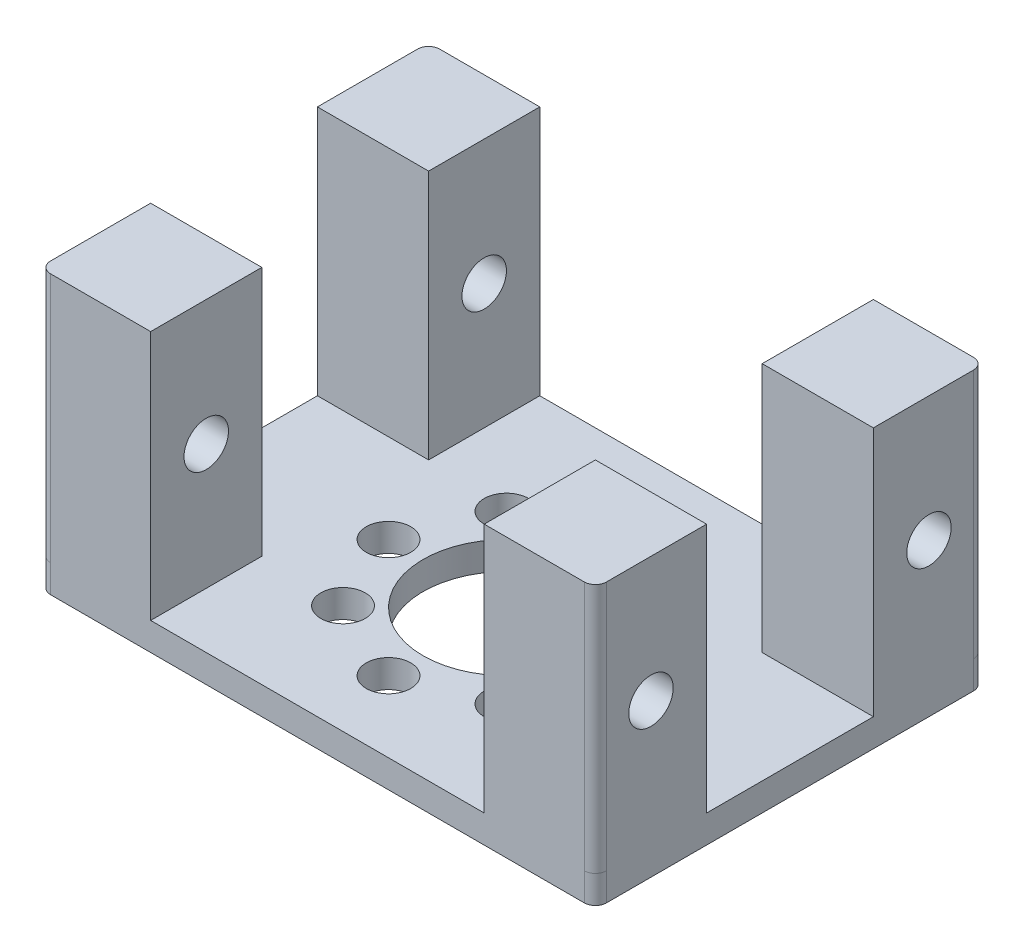
SolidWorks part; units mm, degrees
ref_plane "Front Plane" through (0, 0, 0) normal (0, 0, 1) x (1, 0, 0)
ref_plane "Top Plane" through (0, 0, 0) normal (0, 1, 0) x (1, 0, 0)
ref_plane "Right Plane" through (0, 0, 0) normal (1, 0, 0) x (0, 0, -1)
sketch "Sketch1" plane through (0, 0, 0) normal (0, 1, 0) x (1, 0, 0)
  line L1 (-2, 0) -> (-98, 0)
  line L2 (0, -2) -> (0, -68)
  line L3 (-2, -70) -> (-98, -70)
  line L4 (-100, -2) -> (-100, -68)
  arc A0 (-98, 0) -> (-100, -2) centre (-98, -2) ccw
  circle A1 centre (-50, -36) radius 15
  circle A2 centre (-35, -21) radius 4
  circle A3 centre (-65, -21) radius 4
  circle A4 centre (-65, -50.3968) radius 4
  circle A5 centre (-35, -51) radius 4
  circle A7 centre (-50, -14.7868) radius 4
  circle A8 centre (-28.7868, -36) radius 4
  circle A9 centre (-50, -57.2132) radius 4
  circle A10 centre (-71.2132, -36) radius 4
  arc A12 (-2, 0) -> (0, -2) centre (-2, -2) cw
  arc A13 (0, -68) -> (-2, -70) centre (-2, -68) cw
  arc A14 (-98, -70) -> (-100, -68) centre (-98, -68) cw
  point P8 (-100, 0)
  point P20 (0, 0)
  point P29 (0, 0)
  dimension "D1" = 2
extrude "Boss-Extrude1" add sketch "Sketch1" along normal blind 5
sketch "Sketch4" plane through (0, 0, 0) normal (1, 0, 0) x (0, 0, -1)
  line L1 (0, 5) -> (-20, 5)
  line L2 (0, 5) -> (0, 50)
  line L3 (0, 50) -> (-20, 50)
  line L4 (-20, 5) -> (-20, 50)
  line L5 (-70, 5) -> (-50, 5)
  line L6 (-70, 5) -> (-70, 50)
  line L7 (-70, 50) -> (-50, 50)
  line L8 (-50, 5) -> (-50, 50)
  circle A0 centre (-10, 27.5) radius 4
  circle A1 centre (-60, 27.5) radius 4
  dimension "D3" = 20
  dimension "D1" = 20
  dimension "D2" = 45
extrude "Boss-Extrude2" add sketch "Sketch4" against normal blind 20
sketch "Sketch5" plane through (0, 0, 0) normal (1, 0, 0) x (0, 0, -1)
  line L1 (-70, 5) -> (-50, 5)
  line L2 (-70, 5) -> (-70, 50)
  line L3 (-70, 50) -> (-50, 50)
  line L4 (-50, 5) -> (-50, 50)
  line L5 (-20, 5) -> (0, 5)
  line L6 (-20, 5) -> (-20, 50)
  line L7 (-20, 50) -> (0, 50)
  line L8 (0, 5) -> (0, 50)
  line L10 (0, 5) -> (-20, 5)
  line L11 (0, 5) -> (0, 50)
  line L12 (0, 50) -> (-20, 50)
  line L13 (-20, 5) -> (-20, 50)
  circle A0 centre (-60, 27.5) radius 4
  circle A1 centre (-10, 27.5) radius 4
sketch3d "3DSketch2"
  point P0 (-100, 1.3238, 19.1023)
ref_plane "Plane2" through (-100, 0, 0) normal (-1, 0, 0) x (0, 0, 1)
sketch "Sketch6" plane through (-100, 0, 0) normal (-1, 0, 0) x (0, 0, 1)
  line L1 (0, 5) -> (20, 5)
  line L2 (0, 5) -> (0, 50)
  line L3 (0, 50) -> (20, 50)
  line L4 (20, 5) -> (20, 50)
  line L5 (50, 5) -> (70, 5)
  line L6 (50, 5) -> (50, 50)
  line L7 (50, 50) -> (70, 50)
  line L8 (70, 5) -> (70, 50)
  circle A0 centre (10, 27.5) radius 4
  circle A1 centre (60, 27.5) radius 4
extrude "Boss-Extrude3" add sketch "Sketch6" against normal blind 20
fillet "Fillet1" radius 2 2 edges at (-100, 27.5, 70) (-100, 27.5, 0)
fillet "Fillet2" radius 2 1 edges at (0, 27.5, 0)
fillet "Fillet3" radius 2 1 edges at (0, 27.5, 70)
